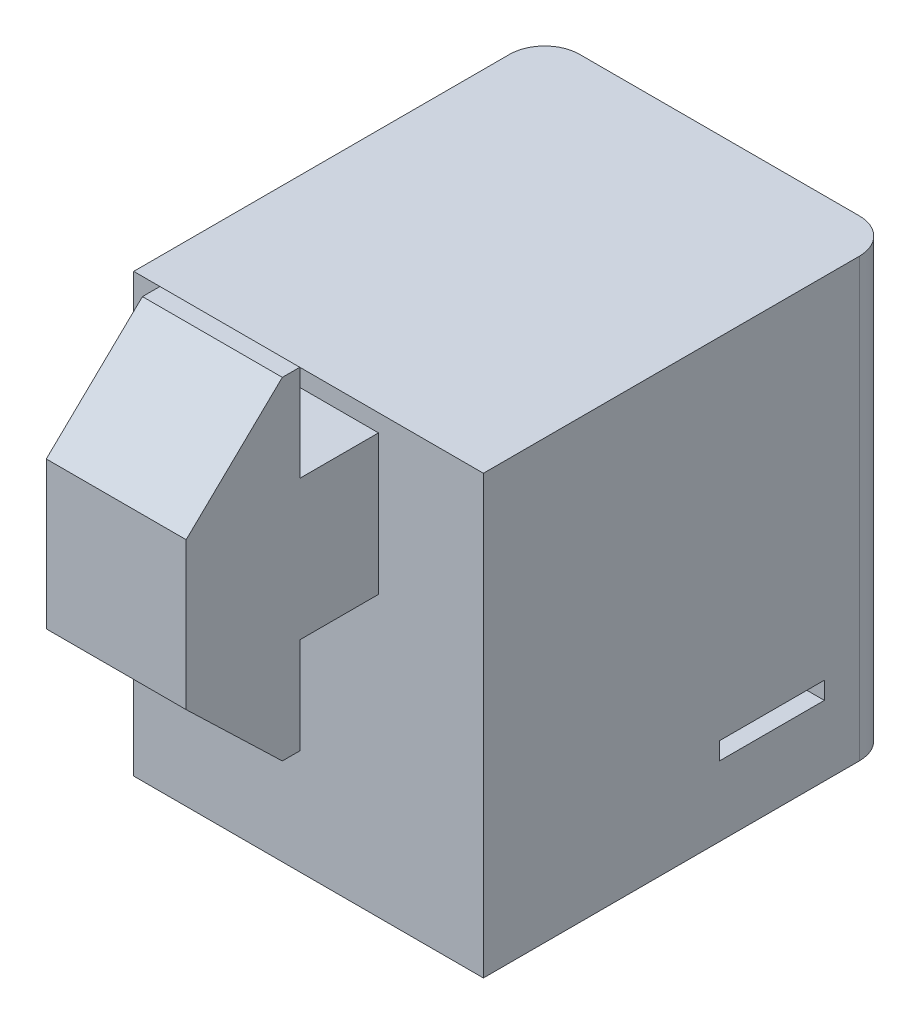
SolidWorks part; units mm, degrees
ref_plane "Piano frontale" through (0, 0, 0) normal (0, 0, 1) x (1, 0, 0)
ref_plane "Piano superiore" through (0, 0, 0) normal (0, 1, 0) x (1, 0, 0)
ref_plane "Piano destro" through (0, 0, 0) normal (1, 0, 0) x (0, 0, -1)
ref_plane "Piano1" through (4, 0, 0) normal (1, 0, 0) x (0, 0, -1)
sketch "Schizzo1" plane through (4, 0, 0) normal (1, 0, 0) x (0, 0, -1)
  line L0 (-5.5, -9.5) -> (-5.5, -4.2084)
  line L1 (-5.5, -4.2084) -> (-11, -4.2084)
  line L2 (-11, -4.2084) -> (-5.5, -9.5)
extrude "Estrusione-Estrusione1" add sketch "Schizzo1" against normal blind 8
sketch "Schizzo2" plane through (0, -4.2084, 0) normal (0, 1, 0) x (-1, 0, 0)
  line L0 (10, 5.5) -> (-4, 5.5)
  line L1 (-4, 5.5) -> (-4, 11)
  line L2 (-4, 11) -> (10, 11)
  line L3 (10, 11) -> (10, 5.5)
extrude "Estrusione-Estrusione2" add sketch "Schizzo2" along normal blind 9.2084
sketch "Schizzo3" plane through (0, -4.2084, 0) normal (0, -1, 0) x (1, 0, 0)
  line L0 (-10, 5.5) -> (-10, 11)
  line L1 (-10, 11) -> (-4, 11)
  line L2 (-4, 11) -> (-4, 5.5)
  line L3 (-4, 5.5) -> (-10, 5.5)
extrude "Estrusione-Estrusione3" add sketch "Schizzo3" along normal blind 5.2916
sketch "Schizzo4" plane through (0, 0, 5.5) normal (0, 0, -1) x (-1, 0, 0)
  line L0 (-4, 5) -> (10, 5)
  line L1 (10, 5) -> (10, -9.5)
  line L2 (10, -9.5) -> (-4, -9.5)
  line L3 (-4, -9.5) -> (-4, 5)
extrude "Estrusione-Estrusione4" add sketch "Schizzo4" along normal blind 5.5
sketch "Schizzo5" plane through (0, 5, 0) normal (0, 1, 0) x (-1, 0, 0)
  line L0 (10, 0) -> (-4, 0)
  line L1 (-4, 4.5) -> (-4, 11)
  line L2 (-4, 11) -> (10, 11)
  spline S0 degree 3 poles (-4, 4.5) (-4, 3) (-4, 1.5) (-4, 0) knots 0 0 0 0 1 1 1 1
  spline S1 degree 3 poles (10, 11) (10, 9.1667) (10, 7.3333) (10, 5.5) knots 0 0 0 0 1 1 1 1
  spline S2 degree 3 poles (10, 5.5) (10, 5.1667) (10, 4.8333) (10, 4.5) knots 0 0 0 0 1 1 1 1
  spline S3 degree 3 poles (10, 4.5) (10, 3) (10, 1.5) (10, 0) knots 0 0 0 0 1 1 1 1
extrude "Estrusione-Estrusione5" add sketch "Schizzo5" along normal blind 4.5
sketch "Schizzo6" plane through (4, 0, 0) normal (1, 0, 0) x (0, 0, -1)
  line L0 (-11, 4.2084) -> (-5.5, 9.5)
  line L1 (-5.5, 9.5) -> (-11, 9.5)
  line L2 (-11, 9.5) -> (-11, 4.2084)
extrude "Taglio-Estrusione1" cut sketch "Schizzo6" against normal blind 8
sketch "Schizzo7" plane through (0, 0, 11) normal (0, 0, 1) x (1, 0, 0)
  line L0 (-10, -9.5) -> (-4, -9.5)
  line L1 (-4, -9.5) -> (-4, 9.5)
  line L2 (-4, 9.5) -> (-10, 9.5)
  line L3 (-10, 5) -> (-10, -9.5)
  spline S0 degree 3 poles (-10, 9.5) (-10, 8) (-10, 6.5) (-10, 5) knots 0 0 0 0 1 1 1 1
extrude "Taglio-Estrusione2" cut sketch "Schizzo7" against normal blind 5.5
sketch "Schizzo8" plane through (0, 0, 0) normal (0, 0, -1) x (-1, 0, 0)
  line L0 (-4, -9.5) -> (-4, 9.5)
  line L1 (-4, 9.5) -> (10, 9.5)
  line L2 (10, 9.5) -> (10, -9.5)
  line L3 (10, -9.5) -> (-4, -9.5)
extrude "Estrusione-Estrusione6" add sketch "Schizzo8" along normal blind 23.5
sketch "Schizzo9" plane through (0, -9.5, 0) normal (0, -1, 0) x (1, 0, 0)
  line L0 (4, -23.5) -> (-10, -23.5)
  line L1 (-10, -23.5) -> (-10, 0)
  line L2 (-10, 5.5) -> (4, 5.5)
  line L3 (4, 0) -> (4, -23.5)
  spline S0 degree 3 poles (-10, 4.5) (-10, 3) (-10, 1.5) (-10, 0) knots 0 0 0 0 1 1 1 1
  spline S1 degree 3 poles (-10, 5.5) (-10, 5.1667) (-10, 4.8333) (-10, 4.5) knots 0 0 0 0 1 1 1 1
  spline S2 degree 3 poles (4, 5.5) (4, 5.1667) (4, 4.8333) (4, 4.5) knots 0 0 0 0 1 1 1 1
  spline S3 degree 3 poles (4, 4.5) (4, 3) (4, 1.5) (4, 0) knots 0 0 0 0 1 1 1 1
extrude "Estrusione-Estrusione7" add sketch "Schizzo9" along normal blind 10.5
sketch "Schizzo10" plane through (0, 9.5, 0) normal (0, 1, 0) x (-1, 0, 0)
  line L0 (10, -23.5) -> (10, 0)
  line L1 (10, 5.5) -> (4, 5.5)
  line L2 (4, 5.5) -> (4, 4.5)
  line L3 (4, 4.5) -> (-4, 4.5)
  line L4 (-4, 0) -> (-4, -23.5)
  line L5 (-4, -23.5) -> (10, -23.5)
  spline S0 degree 3 poles (10, 4.5) (10, 3) (10, 1.5) (10, 0) knots 0 0 0 0 1 1 1 1
  spline S1 degree 3 poles (10, 5.5) (10, 5.1667) (10, 4.8333) (10, 4.5) knots 0 0 0 0 1 1 1 1
  spline S2 degree 3 poles (-4, 4.5) (-4, 3) (-4, 1.5) (-4, 0) knots 0 0 0 0 1 1 1 1
extrude "Taglio-Estrusione3" cut sketch "Schizzo10" against normal blind 4.5
sketch "Schizzo11" plane through (0, 0, 5.5) normal (0, 0, 1) x (1, 0, 0)
  line L0 (-4, -9.5) -> (-4, 5)
  line L1 (-4, 5) -> (-10, 5)
  line L2 (-10, 5) -> (-10, -20)
  line L3 (-10, -20) -> (4, -20)
  line L4 (4, -20) -> (4, -9.5)
  line L5 (4, -9.5) -> (-4, -9.5)
extrude "Taglio-Estrusione4" cut sketch "Schizzo11" against normal blind 1
sketch "Schizzo12" plane through (0, 0, 4.5) normal (0, 0, 1) x (1, 0, 0)
  line L0 (4, 4) -> (4, 5)
  line L1 (4, 5) -> (-10, 5)
  line L2 (-10, 5) -> (-10, -20)
  line L3 (-10, -20) -> (4, -20)
  line L4 (4, -20) -> (4, -4)
  line L5 (4, -4) -> (-4, -4)
  line L6 (-4, -4) -> (-4, 4)
  line L7 (-4, 4) -> (4, 4)
extrude "Taglio-Estrusione5" cut sketch "Schizzo12" against normal blind 4.5
sketch "Schizzo13" plane through (4, 0, 0) normal (1, 0, 0) x (0, 0, -1)
  line L0 (23.5, -20) -> (0, -20)
  line L1 (0, -20) -> (0, 5)
  line L2 (0, 5) -> (23.5, 5)
  line L3 (23.5, 5) -> (23.5, -20)
extrude "Estrusione-Estrusione8" add sketch "Schizzo13" along normal blind 6
sketch "Schizzo14" plane through (-10, 0, 0) normal (-1, 0, 0) x (0, 0, 1)
  line L0 (-13.5, -16) -> (-13.5, -15)
  line L1 (-13.5, -15) -> (-19.5, -15)
  line L2 (-19.5, -15) -> (-19.5, -16)
  line L3 (-19.5, -16) -> (-13.5, -16)
extrude "Taglio-Estrusione6" cut sketch "Schizzo14" against normal blind 5
sketch "Schizzo15" plane through (0, -20, 0) normal (0, -1, 0) x (1, 0, 0)
  line L0 (3.1, -11.9) -> (3.1, -8.1)
  line L1 (-3.1, -8.1) -> (-3.1, -11.9)
  arc A0 (-3.1, -11.9) -> (3.1, -11.9) centre (0, -11.9) ccw
  arc A1 (3.1, -8.1) -> (-3.1, -8.1) centre (0, -8.1) ccw
extrude "Taglio-Estrusione7" cut sketch "Schizzo15" against normal blind 14
sketch "Schizzo16" plane through (10, 0, 0) normal (1, 0, 0) x (0, 0, -1)
  line L0 (13.5, -15) -> (13.5, -16)
  line L1 (13.5, -16) -> (19.5, -16)
  line L2 (19.5, -16) -> (19.5, -15)
  line L3 (19.5, -15) -> (13.5, -15)
extrude "Taglio-Estrusione8" cut sketch "Schizzo16" against normal blind 5
fillet "Raccordo1" radius 2 2 edges at (10, -7.5, -23.5) (-10, -7.5, -23.5)
